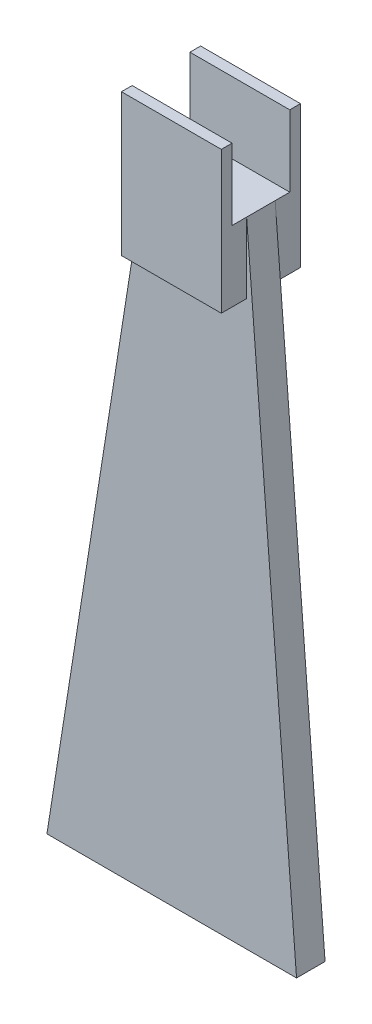
SolidWorks part; units mm, degrees
material "Gray Cast Iron"
ref_plane "Front Plane" through (0, 0, 0) normal (0, 0, 1) x (1, 0, 0)
ref_plane "Top Plane" through (0, 0, 0) normal (0, 1, 0) x (1, 0, 0)
ref_plane "Right Plane" through (0, 0, 0) normal (1, 0, 0) x (0, 0, -1)
sketch "Sketch1" plane through (0, 0, 0) normal (0, 0, 1) x (1, 0, 0)
  line L0 (-115, 0) -> (-45, 0)
  line L1 (-45, 0) -> (-59, 177.8)
  line L2 (-59, 177.8) -> (-87, 177.8)
  line L3 (-87, 177.8) -> (-115, 0)
extrude "Boss-Extrude1" add sketch "Sketch1" along normal mid plane 8
sketch "Sketch2" plane through (0, 0, 0) normal (0, 1, 0) x (1, 0, 0)
  line L0 (-87, -11.1) -> (-59, -11.1)
  line L1 (-59, -11.1) -> (-59, 11.1)
  line L2 (-59, 11.1) -> (-87, 11.1)
  line L3 (-87, 11.1) -> (-87, -11.1)
extrude "Boss-Extrude2" add sketch "Sketch2" along normal blind 19.8 from offset 158
sketch "Sketch3" plane through (0, 0, 0) normal (0, 1, 0) x (1, 0, 0)
  line L0 (-87, 8.1) -> (-59, 8.1)
  line L1 (-87, 11.1) -> (-87, 4) construction
  line L2 (-59, 4) -> (-59, 11.1) construction
  line L3 (-59, 8.1) -> (-59, 11.1)
  line L4 (-59, 11.1) -> (-87, 11.1)
  line L5 (-87, 11.1) -> (-87, 8.1)
  line L6 (-87, -8.1) -> (-59, -8.1)
  line L7 (-87, -4) -> (-87, -11.1) construction
  line L8 (-59, -11.1) -> (-59, -4) construction
  line L9 (-59, -8.1) -> (-59, -11.1)
  line L10 (-59, -11.1) -> (-87, -11.1)
  line L11 (-87, -11.1) -> (-87, -8.1)
extrude "Boss-Extrude3" add sketch "Sketch3" along normal blind 20 from offset 177.8
